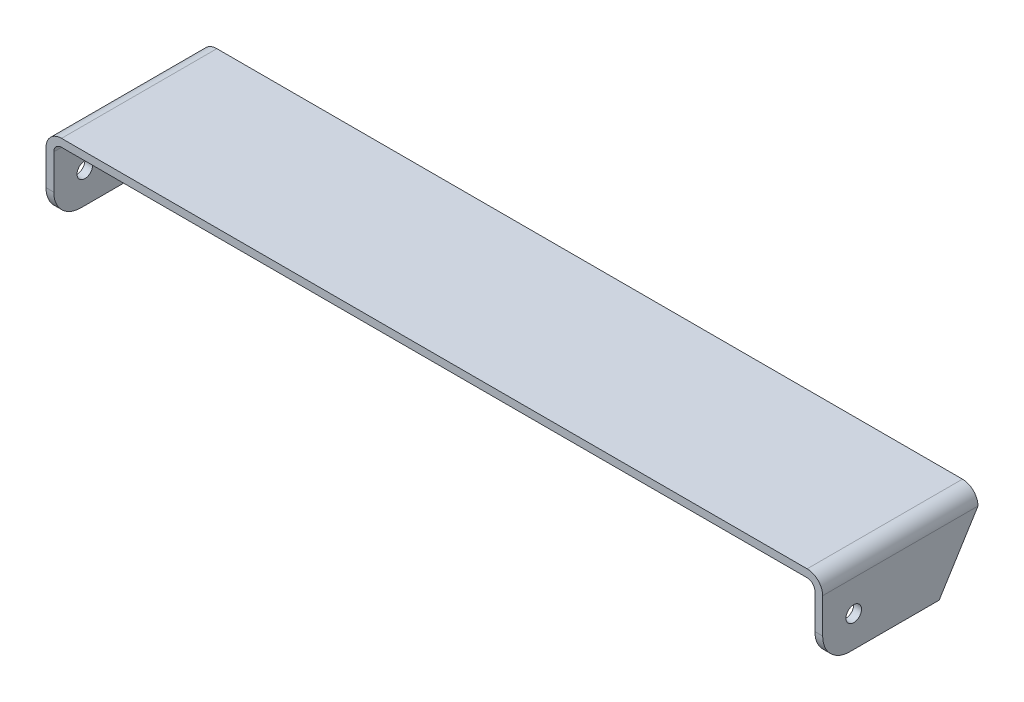
SolidWorks part; units mm, degrees
ref_plane "Front Plane" through (0, 0, 0) normal (0, 0, 1) x (1, 0, 0)
ref_plane "Top Plane" through (0, 0, 0) normal (0, 1, 0) x (1, 0, 0)
ref_plane "Right Plane" through (0, 0, 0) normal (1, 0, 0) x (0, 0, -1)
sketch "Sketch2" plane through (0, 0, 0) normal (0, 0, 1) x (1, 0, 0)
  line L0 (-500, 0) -> (-500, 80)
  line L1 (-480, 100) -> (480, 100)
  line L2 (500, 80) -> (500, 0)
  arc A0 (500, 80) -> (480, 100) centre (480, 80) ccw
  arc A1 (-480, 100) -> (-500, 80) centre (-480, 80) ccw
  point P7 (500, 100)
  point P10 (-500, 100)
  dimension "D4" = 20
  dimension "D6" = 500
  dimension "D1" = 1000
  dimension "D2" = 500
  dimension "D3" = 100
  dimension "D5" = 100
extrude "Extrude-Thin1" add sketch "Sketch2" along normal mid plane 200 thin
sketch "Sketch3" plane through (-500, 0, 0) normal (-1, 0, 0) x (0, 0, 1)
  line L0 (-100, 80) -> (-100, 0)
  line L1 (-100, 0) -> (-100, 80) construction
  line L2 (-100, 0) -> (-50, 0)
  line L3 (100, 0) -> (-100, 0) construction
  line L4 (-50, 0) -> (-100, 80)
  dimension "D1" = 80
  dimension "D2" = 50
extrude "Cut-Extrude1" cut sketch "Sketch3" against normal blind 1218
sketch "Sketch4" plane through (-500, 0, 0) normal (-1, 0, 0) x (0, 0, 1)
  line L0 (100, 100) -> (-100, 100) construction
  line L1 (100, 0) -> (100, 80) construction
  circle A0 centre (60, 40) radius 10
  dimension "D3" = 20
  dimension "D1" = 60
  dimension "D2" = 40
extrude "Cut-Extrude2" cut sketch "Sketch4" against normal blind 1285
fillet "Fillet1" radius 35 2 edges at (495, 0, 100) (-495, 0, 100)
